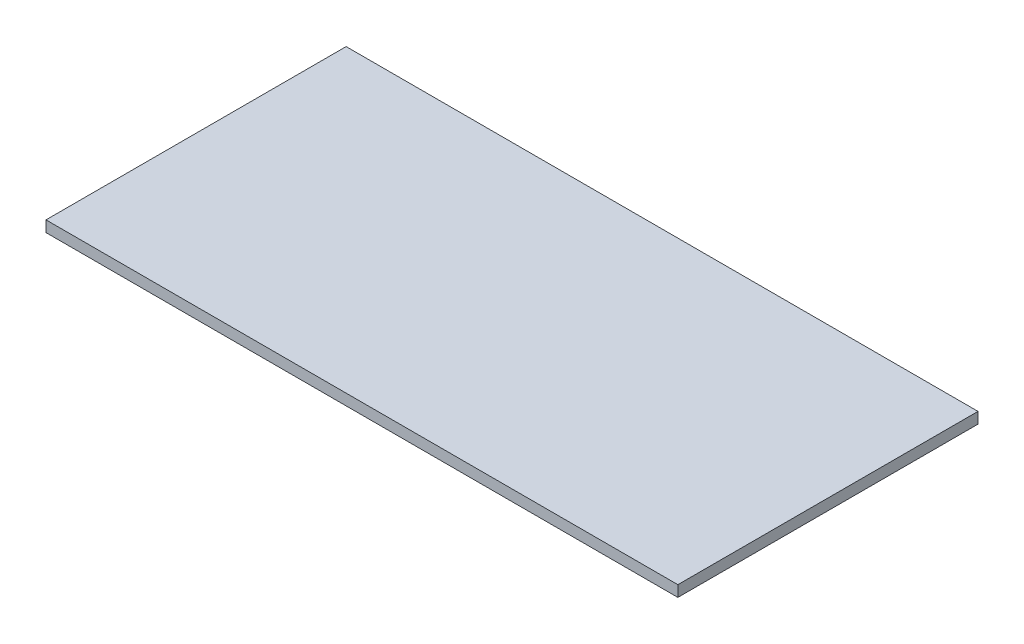
SolidWorks part; units mm, degrees
ref_plane "前视基准面" through (0, 0, 0) normal (0, 0, 1) x (1, 0, 0)
ref_plane "上视基准面" through (0, 0, 0) normal (0, 1, 0) x (1, 0, 0)
ref_plane "右视基准面" through (0, 0, 0) normal (1, 0, 0) x (0, 0, -1)
sketch "草图1" plane through (0, 0, 0) normal (0, 1, 0) x (1, 0, 0)
  line L1 (0, 0) -> (80, 0)
  line L2 (0, 0) -> (0, 38)
  line L3 (0, 38) -> (80, 38)
  line L4 (80, 0) -> (80, 38)
  dimension "D1" = 80
  dimension "D2" = 38
extrude "凸台-拉伸1" add sketch "草图1" along normal blind 1.4
